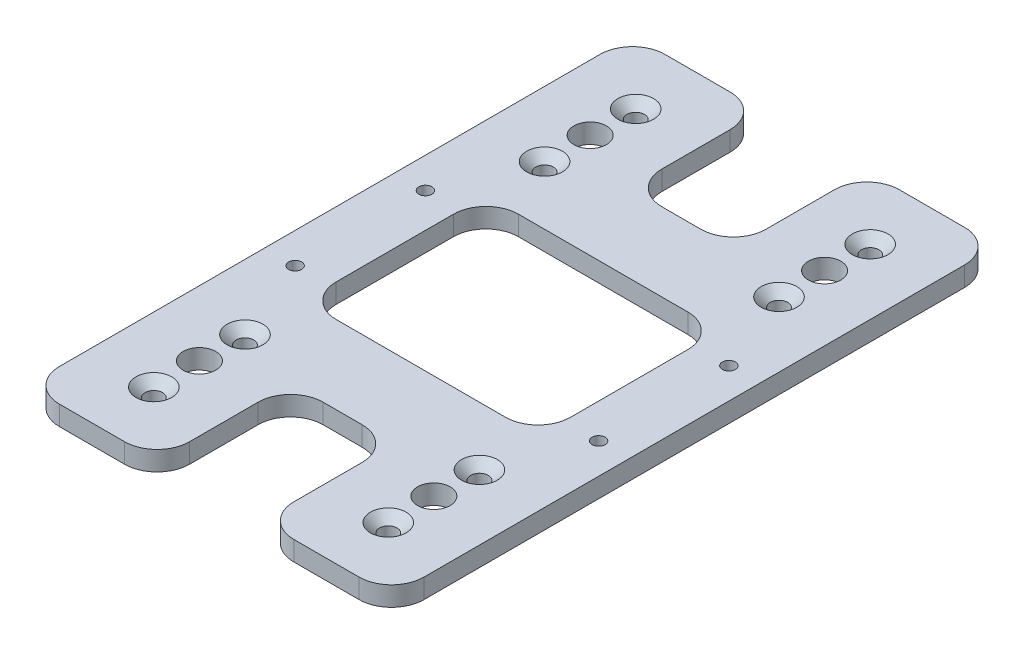
SolidWorks part; units mm, degrees
ref_plane "Front Plane" through (0, 0, 0) normal (0, 0, 1) x (1, 0, 0)
ref_plane "Top Plane" through (0, 0, 0) normal (0, 1, 0) x (1, 0, 0)
ref_plane "Right Plane" through (0, 0, 0) normal (1, 0, 0) x (0, 0, -1)
sketch "Sketch1" plane through (0, 0, 0) normal (0, 1, 0) x (1, 0, 0)
  line L0 (0, 46.9794) -> (0, -46.0206) construction
  line L1 (8, 26) -> (-8, 26)
  line L2 (-8, 26) -> (-8, 46.5)
  line L3 (-8, 46.5) -> (-28, 46.5)
  line L4 (-28, 46.5) -> (-28, -46.5)
  line L5 (-81.4948, 0) -> (81.4948, 0) construction
  line L6 (-8, -46.5) -> (-28, -46.5)
  line L7 (-8, -26) -> (-8, -46.5)
  line L8 (8, -26) -> (-8, -26)
  line L9 (8, -26) -> (8, -46.5)
  line L10 (8, -46.5) -> (28, -46.5)
  line L11 (28, 46.5) -> (28, -46.5)
  line L12 (8, 46.5) -> (28, 46.5)
  line L13 (8, 26) -> (8, 46.5)
  point P3 (28, 0)
  point P16 (-28, 0)
  point P20 (0, -26)
  point P25 (0, 26)
  dimension "D1" = 93
  dimension "D2" = 28
  dimension "D3" = 20
  dimension "D4" = 26
  dimension "D5" = 46.5
extrude "Boss-Extrude1" add sketch "Sketch1" along normal blind 3
fillet "Fillet1" radius 5 12 edges at (-28, 1.5, -46.5) (-28, 1.5, 46.5) (-8, 1.5, 46.5) (-8, 1.5, 26) (8, 1.5, 26) (8, 1.5, 46.5) (28, 1.5, 46.5) (28, 1.5, -46.5) (8, 1.5, -46.5) (-8, 1.5, -46.5) (8, 1.5, -26) (-8, 1.5, -26)
sketch "Sketch3" plane through (0, 3, 0) normal (0, 1, 0) x (1, 0, 0)
  line L0 (-13, 46.5) -> (-23, 46.5) construction
  line L1 (-28, 41.5) -> (-28, -41.5) construction
  line L3 (-18, 37) -> (-18, 23) construction
  circle A3 centre (-18, 37) radius 1.35
  circle A4 centre (-18, 23) radius 1.35
  circle A5 centre (-18, 30) radius 2.5
  dimension "D9" = 2.7
  dimension "D10" = 2.7
  dimension "D11" = 5
  dimension "D12" = 10
  dimension "D13" = 9.5
  dimension "D14" = 14
sketch "Sketch5" plane through (0, 3, 0) normal (0, 1, 0) x (1, 0, 0)
  line L0 (-18, 46.5) -> (-18, -46.5) construction
  line L1 (18, -14) -> (-18, -14)
  line L2 (18, -14) -> (18, 14)
  line L3 (18, 14) -> (-18, 14)
  line L4 (-18, -14) -> (-18, 14)
  line L5 (18, -14) -> (-18, 14) construction
  line L6 (18, 14) -> (-18, -14) construction
  line L7 (3, 26) -> (-3, 26) construction
  line L8 (-13, 46.5) -> (-23, 46.5) construction
  line L9 (-23, -46.5) -> (-13, -46.5) construction
  point P0 (0, 0)
  dimension "D1" = 12
extrude "Cut-Extrude1" cut sketch "Sketch5" against normal up to next
fillet "Fillet2" radius 5 4 edges at (18, 1.5, 14) (-18, 1.5, 14) (-18, 1.5, -14) (18, 1.5, -14)
hole_wizard "CSK for M2.5 Countersunk Flat Head Screw1" positions "3DSketch1" profile "Sketch6" countersink size "M2.5" standard "DIN" end condition up to next
sketch3d "3DSketch1"
  point P0 (-18, 3, -37)
  point P3 (-18, 3, -23)
sketch "Sketch6" plane through (-18, 3, -37) normal (1, 0, 0) x (0, 0, 1)
  line L0 (0, 0) -> (0, 3)
  line L1 (0, 3) -> (1.35, 3)
  line L2 (1.35, 3) -> (1.35, 1.4)
  line L3 (1.35, 1.4) -> (2.75, 0)
  line L5 (2.75, 0) -> (0, 0)
  line L6 (-1.35, 1.4) -> (-2.75, 0) construction
  line L11 (0, -6.35) -> (0, 107.95) construction
  dimension "Thru Hole Dia." = 2.7
  dimension "Thru Hole Depth" = 3
  dimension "Near C'Sink Dia." = 5.5
  dimension "Near C'Sink Angle" = 90
extrude "Cut-Extrude2" cut sketch "Sketch3" against normal up to next contours A5
mirror "Mirror1" about plane through (0, 0, 0) normal (1, 0, 0) of "Cut-Extrude2", "CSK for M2.5 Countersunk Flat Head Screw1" second plane through (0, 0, 0) second plane normal (0, 0, 1)
sketch "Sketch7" plane through (0, 3, 0) normal (0, 1, 0) x (1, 0, 0)
  circle A0 centre (-23.3, 10) radius 1
  dimension "D1" = 2
  dimension "D2" = 23.3
  dimension "D3" = 10
extrude "Cut-Extrude3" cut sketch "Sketch7" against normal up to next
mirror "Mirror2" about plane through (0, 0, 0) normal (1, 0, 0) of "Cut-Extrude3" second plane through (0, 0, 0) second plane normal (0, 0, 1)
